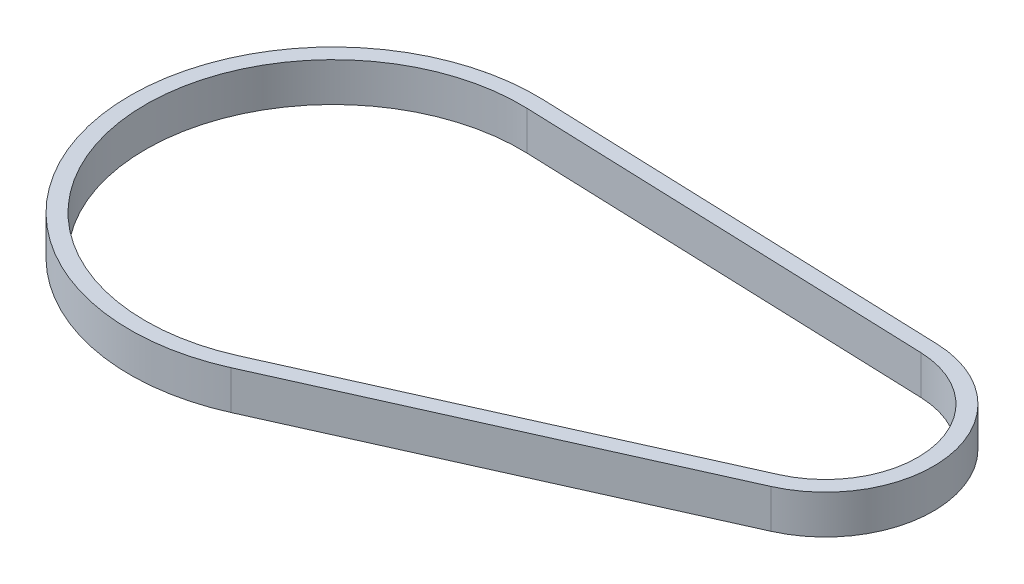
SolidWorks part; units mm, degrees
ref_plane "Front Plane" through (0, 0, 0) normal (0, 0, 1) x (1, 0, 0)
ref_plane "Top Plane" through (0, 0, 0) normal (0, 1, 0) x (1, 0, 0)
ref_plane "Right Plane" through (0, 0, 0) normal (1, 0, 0) x (0, 0, -1)
sketch "Sketch1" plane through (0, 0, 0) normal (0, 1, 0) x (1, 0, 0)
  line L0 (0, 0) -> (105.9996, 20.69) construction
  line L1 (1.7316, 48.2289) -> (106.8529, 44.4547)
  line L2 (115.727, -1.0095) -> (19.7411, -44.0377)
  line L3 (1.8751, 52.2263) -> (106.9964, 48.4521)
  line L4 (117.3632, -4.6595) -> (21.3773, -47.6877)
  arc A0 (1.7316, 48.2289) -> (19.7411, -44.0377) centre (0, 0) ccw
  arc A1 (115.727, -1.0095) -> (106.8529, 44.4547) centre (105.9996, 20.69) ccw
  arc A2 (117.3632, -4.6595) -> (106.9964, 48.4521) centre (105.9996, 20.69) ccw
  arc A3 (1.8751, 52.2263) -> (21.3773, -47.6877) centre (0, 0) ccw
  dimension "D1" = 96.52
  dimension "D4" = 47.56
  dimension "D2" = 108
  dimension "D3" = 20.69
  dimension "D5" = 4
extrude "Boss-Extrude1" add sketch "Sketch1" along normal blind 10
